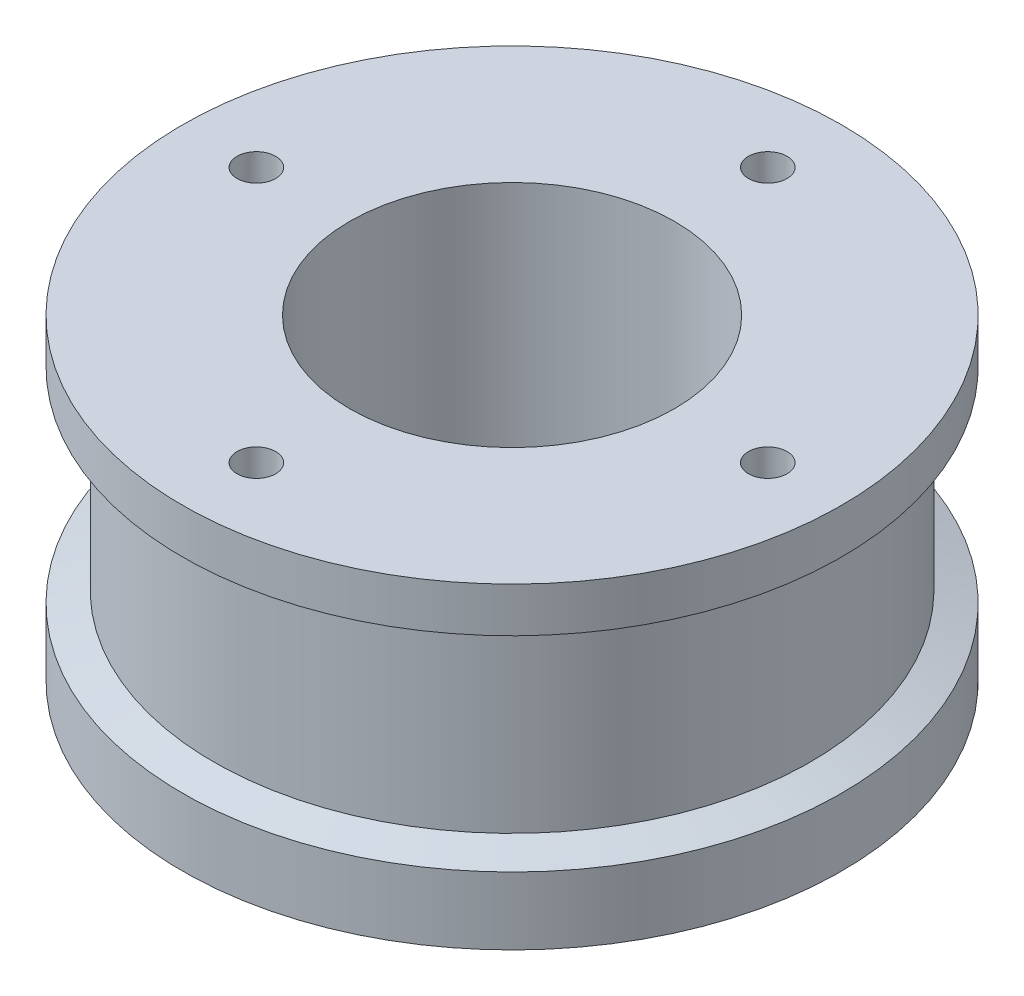
SolidWorks part; units mm, degrees
ref_plane "Front Plane" through (0, 0, 0) normal (0, 0, 1) x (1, 0, 0)
ref_plane "Top Plane" through (0, 0, 0) normal (0, 1, 0) x (1, 0, 0)
ref_plane "Right Plane" through (0, 0, 0) normal (1, 0, 0) x (0, 0, -1)
sketch "Sketch1" plane through (0, 0, 0) normal (0, 0, 1) x (1, 0, 0)
  line L0 (0, 0) -> (0, 26.7041) construction
  line L1 (14.2875, 27.8791) -> (29, 27.8791)
  line L2 (29, 27.8791) -> (29, 23.9405)
  line L3 (29, 0) -> (14.2875, 0)
  line L4 (14.2875, 0) -> (14.2875, 27.8791)
  line L5 (94.2, 13.9396) -> (26.5, 13.9395) construction
  line L6 (29, 23.9405) -> (26.25, 22.9396)
  line L7 (26.25, 22.9396) -> (26.25, 6.9395)
  line L8 (29, 5.9386) -> (26.25, 6.9395)
  line L9 (29, 5.9386) -> (29, 0)
  dimension "D1" = 29
  dimension "D2" = 27.8791
  dimension "D3" = 14.2875
  dimension "D4" = 67.7
  dimension "D5" = 94.2
  dimension "D6" = 16
  dimension "D7" = 70
  dimension "D8" = 0.25
  dimension "D9" = 6.9396
  dimension "D10" = 70
revolve "Revolve1" add sketch "Sketch1" angle 360 about L0
sketch "Sketch2" plane through (0, 0, 0) normal (0, 1, 0) x (1, 0, 0)
  circle A0 centre (0, 0) radius 22.5 construction
  point P3 (0, 22.5)
  point P4 (22.5, 0)
  point P5 (-22.5, 0)
  point P6 (0, -22.5)
  dimension "D1" = 45
hole_wizard "CBORE for M3 SBHCS1" positions "Sketch2" profile "Sketch3" counterbore size "M3" standard "ANSI Metric" end condition up to next
sketch "Sketch3" plane through (0, 0, 22.5) normal (1, 0, 0) x (0, 0, -1)
  line L0 (0, 0) -> (0, 27.8791)
  line L1 (0, 27.8791) -> (1.7, 27.8791)
  line L3 (1.7, 27.8791) -> (1.7, 2.15)
  line L4 (1.7, 2.15) -> (3.35, 2.15)
  line L5 (3.35, 2.15) -> (3.35, 0)
  line L7 (3.35, 0) -> (0, 0)
  line L11 (0, -6.35) -> (0, 107.95) construction
  dimension "Thru Hole Dia." = 3.4
  dimension "Thru Hole Depth" = 27.8791
  dimension "C'Bore Dia." = 6.7
  dimension "C'Bore Depth" = 2.15
sketch "Sketch4" plane through (0, 0, 0) normal (0, 1, 0) x (1, 0, 0)
  circle A0 centre (0, 0) radius 23.8125 construction
  point P2 (-11.9063, 20.6222)
  point P7 (11.9062, 20.6222)
  point P8 (23.8125, 0)
  point P9 (11.9063, -20.6222)
  point P10 (-11.9062, -20.6222)
  point P11 (-23.8125, 0)
  point P12 (0, 0)
  dimension "D1" = 47.625
  dimension "D2" = 6
hole_wizard "F (0.257) Diameter Hole1" positions "Sketch4" profile "Sketch6" hole size "F" standard "ANSI Inch"
sketch "Sketch6" plane through (-11.9062, 0, 20.6222) normal (1, 0, 0) x (0, 0, -1)
  line L0 (0, 0) -> (0, 8.3111)
  line L1 (0, 8.3111) -> (3.2639, 6.35)
  line L2 (3.2639, 6.35) -> (3.2639, 0)
  line L5 (3.2639, 0) -> (0, 0)
  line L10 (0, 8.3111) -> (-3.2639, 6.35) construction
  line L11 (0, -6.35) -> (0, 107.95) construction
  dimension "Hole Dia." = 6.5278
  dimension "Hole Depth" = 6.35
  dimension "Drill Angle" = 118
